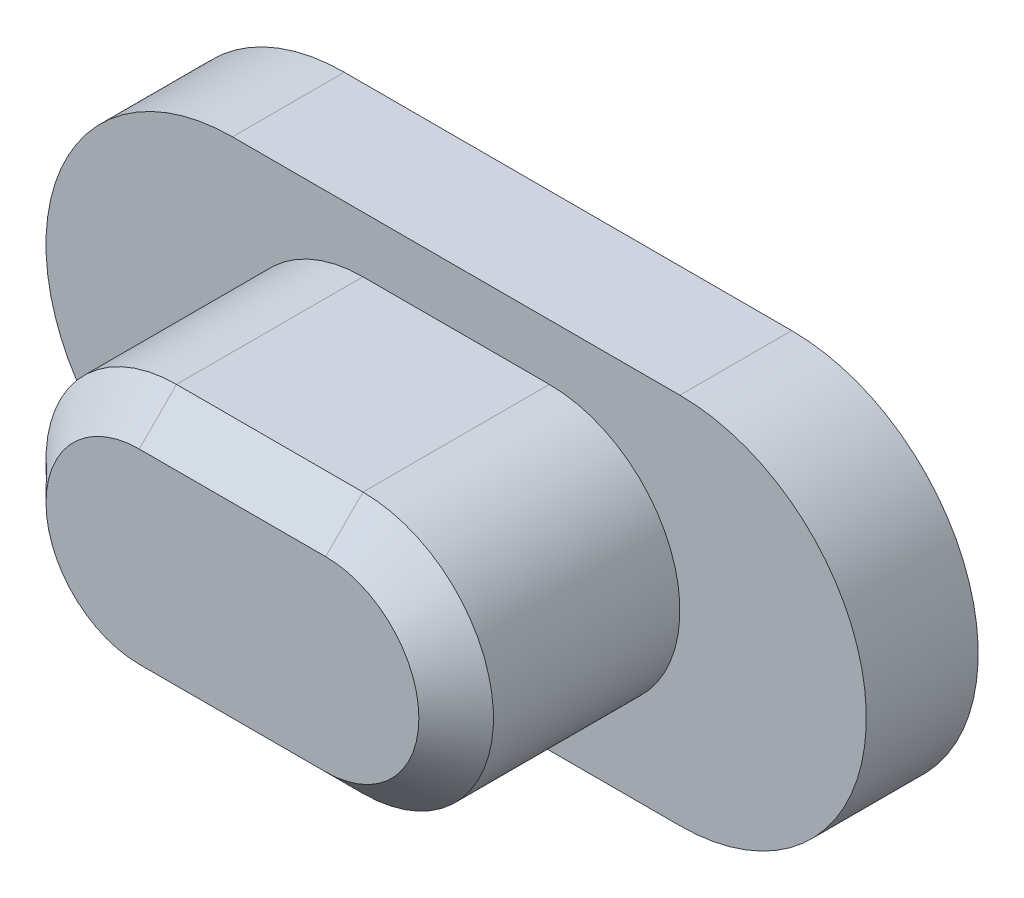
SolidWorks part; units mm, degrees
material "Латунь"
ref_plane "Спереди" through (0, 0, 0) normal (0, 0, 1) x (1, 0, 0)
ref_plane "Сверху" through (0, 0, 0) normal (0, 1, 0) x (1, 0, 0)
ref_plane "Справа" through (0, 0, 0) normal (1, 0, 0) x (0, 0, -1)
sketch "Эскиз1" plane through (0, 0, 0) normal (0, 0, 1) x (1, 0, 0)
  line L0 (-6, 0) -> (6, 0) construction
  line L1 (-6, 5) -> (6, 5)
  line L2 (-6, -5) -> (6, -5)
  arc A0 (-6, 5) -> (-6, -5) centre (-6, 0) ccw
  arc A1 (6, -5) -> (6, 5) centre (6, 0) ccw
  point P2 (0, 0)
  dimension "D1" = 5
  dimension "D2" = 12
extrude "Бобышка-Вытянуть1" add sketch "Эскиз1" along normal blind 3
sketch "Эскиз2" plane through (0, 0, 3) normal (0, 0, 1) x (1, 0, 0)
  line L0 (-2.5, 0) -> (2.5, 0) construction
  line L1 (-2.5, 3.5) -> (2.5, 3.5)
  line L2 (-2.5, -3.5) -> (2.5, -3.5)
  arc A0 (-2.5, 3.5) -> (-2.5, -3.5) centre (-2.5, 0) ccw
  arc A1 (2.5, -3.5) -> (2.5, 3.5) centre (2.5, 0) ccw
  point P3 (0, 0)
  dimension "D1" = 7
  dimension "D2" = 5
extrude "Бобышка-Вытянуть2" add sketch "Эскиз2" along normal blind 6
sketch "Эскиз3" plane through (0, 0, 0) normal (0, 0, -1) x (-1, 0, 0)
  line L0 (0.75, 0) -> (-0.75, 0) construction
  line L1 (0.75, -2) -> (-0.75, -2)
  line L2 (0.75, 2) -> (-0.75, 2)
  arc A0 (0.75, -2) -> (0.75, 2) centre (0.75, 0) ccw
  arc A1 (-0.75, 2) -> (-0.75, -2) centre (-0.75, 0) ccw
  point P3 (0, 0)
  point P9 (0, 0)
  dimension "D1" = 4
  dimension "D2" = 1.5
extrude "Вырез-Вытянуть1" cut sketch "Эскиз3" against normal blind 4
chamfer "Фаска1" distance 1 angle 45 4 edges at (0, 3.5, 9) (-6, 0, 9) (6, 0, 9) (0, -3.5, 9)
ref_plane "Плоскость1" through (11, 0, 0) normal (1, 0, 0) x (0, 0, -1)
